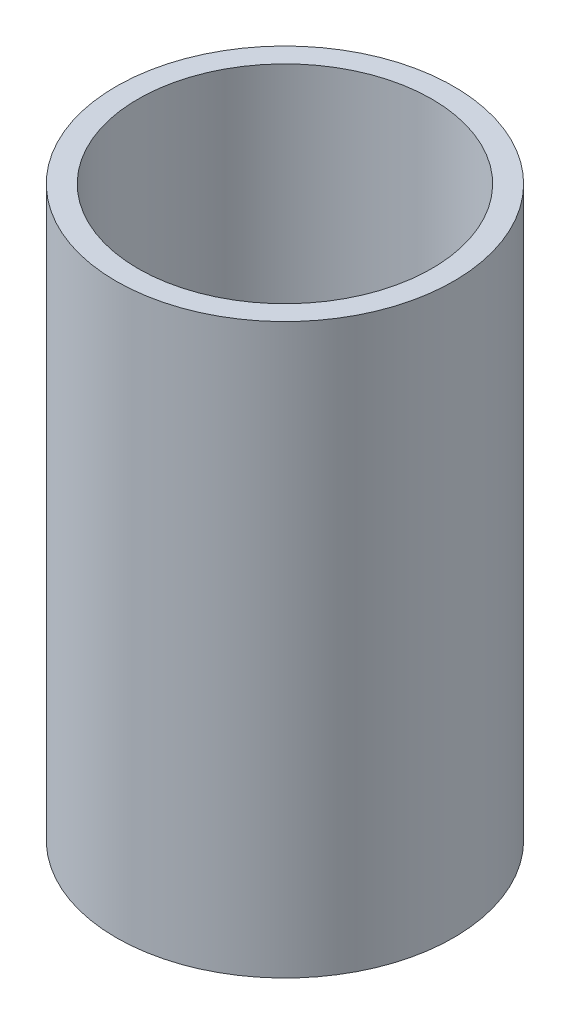
SolidWorks part; units mm, degrees
material "ABS PC"
ref_plane "Front Plane" through (0, 0, 0) normal (0, 0, 1) x (1, 0, 0)
ref_plane "Top Plane" through (0, 0, 0) normal (0, 1, 0) x (1, 0, 0)
ref_plane "Right Plane" through (0, 0, 0) normal (1, 0, 0) x (0, 0, -1)
sketch "Sketch1" plane through (0, 0, 0) normal (0, 1, 0) x (1, 0, 0)
  circle A0 centre (0, 0) radius 30.1625
  circle A1 centre (0, 0) radius 26.2509
  dimension "D1" = 60.325
  dimension "D2" = 52.5018
sketch "Sketch2" plane through (0, 0, 0) normal (1, 0, 0) x (0, 0, -1)
  line L0 (0, 0) -> (0, 101.6)
  dimension "D2" = 101.6
sweep "Sweep1" add profiles "Sketch1" path "Sketch2"
